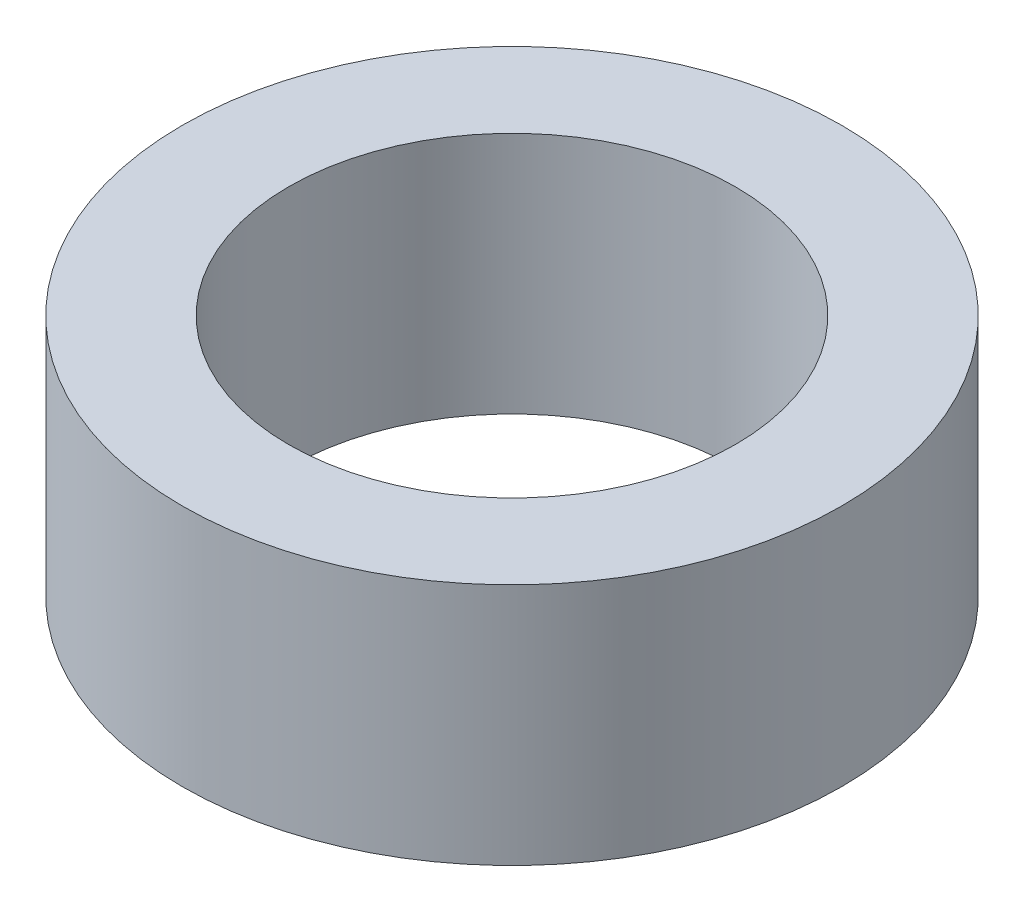
SolidWorks part; units mm, degrees
ref_plane "Front Plane" through (0, 0, 0) normal (0, 0, 1) x (1, 0, 0)
ref_plane "Top Plane" through (0, 0, 0) normal (0, 1, 0) x (1, 0, 0)
ref_plane "Right Plane" through (0, 0, 0) normal (1, 0, 0) x (0, 0, -1)
sketch "Sketch1" plane through (0, 0, 0) normal (0, 1, 0) x (1, 0, 0)
  circle A0 centre (0, 0) radius 3.675
  circle A1 centre (0, 0) radius 5.425
  dimension "D1" = 7.35
  dimension "D2" = 10.85
extrude "Boss-Extrude1" add sketch "Sketch1" along normal blind 4
